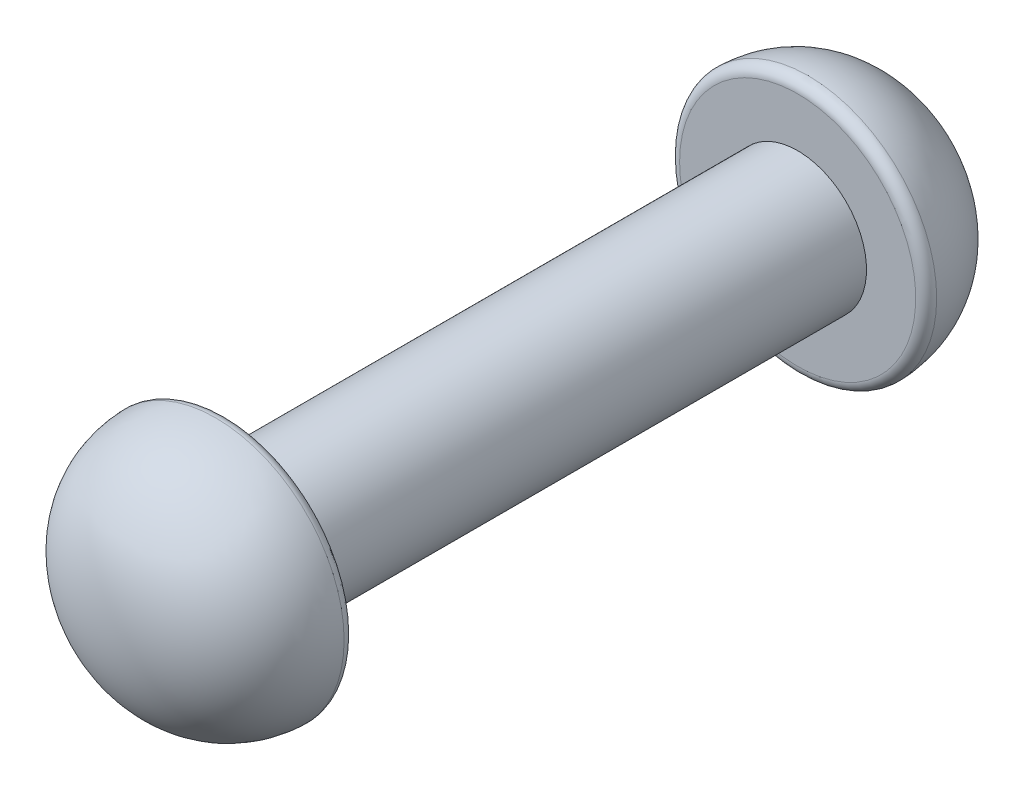
SolidWorks part; units mm, degrees
ref_plane "Front Plane" through (0, 0, 0) normal (0, 0, 1) x (1, 0, 0)
ref_plane "Top Plane" through (0, 0, 0) normal (0, 1, 0) x (1, 0, 0)
ref_plane "Right Plane" through (0, 0, 0) normal (1, 0, 0) x (0, 0, -1)
sketch "Sketch1" plane through (0, 0, 0) normal (0, 0, 1) x (1, 0, 0)
  circle A0 centre (0, 0) radius 1
  dimension "D1" = 2
extrude "Boss-Extrude1" add sketch "Sketch1" along normal blind 8.3
sketch "Sketch2" plane through (0, 0, 0) normal (0, 1, 0) x (1, 0, 0)
  line L0 (0, 4.8363) -> (0, -10.7008) construction
  line L1 (0, 0) -> (1.8625, 0)
  line L3 (0, 1.7085) -> (0, 0)
  line L4 (1, -4.15) -> (6.2153, -4.15) construction
  line L5 (1, -8.3) -> (1, 0) construction
  line L6 (0, -8.3) -> (1.8625, -8.3)
  line L7 (0, -10.0085) -> (0, -8.3)
  line L8 (-1.0639, 1.7085) -> (1.0639, 1.7085) construction
  spline S0 degree 3 poles (1.8625, 0) (1.9168, 0.8407) (1.3298, 1.7085) (0, 1.7085) knots 0 0 0 0 1 1 1 1
  spline S1 degree 3 poles (1.8625, -8.3) (1.9168, -9.1407) (1.3298, -10.0085) (0, -10.0085) knots 0 0 0 0 1 1 1 1
revolve "Revolve1" add sketch "Sketch2" angle 360 about L0
fillet "Fillet1" radius 0.15 1 edges at (-1.8625, 0, 8.3)
fillet "Fillet2" radius 0.15 1 edges at (-1.8625, 0, 0)
